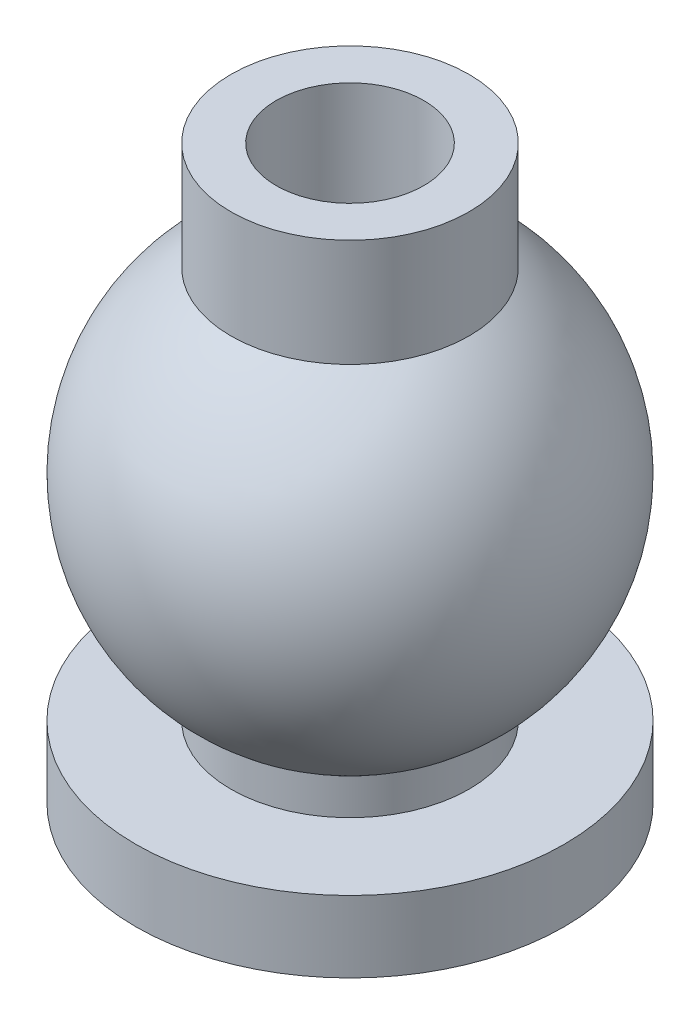
SolidWorks part; units mm, degrees
ref_plane "Front Plane" through (0, 0, 0) normal (0, 0, 1) x (1, 0, 0)
ref_plane "Top Plane" through (0, 0, 0) normal (0, 1, 0) x (1, 0, 0)
ref_plane "Right Plane" through (0, 0, 0) normal (1, 0, 0) x (0, 0, -1)
sketch "Sketch1" plane through (0, 0, 0) normal (0, 0, 1) x (1, 0, 0)
  line L0 (0, 6.8365) -> (0, -6) construction
  line L1 (1.55, -6) -> (4.5, -6)
  line L2 (4.5, -6) -> (4.5, -4.5)
  line L3 (4.5, -4.5) -> (2.5, -4.5)
  line L4 (2.5, -4.5) -> (2.5, -3.7417)
  line L5 (1.55, -6) -> (1.55, 6)
  line L6 (1.55, 6) -> (2.5, 6)
  line L7 (2.5, 6) -> (2.5, 3.7417)
  line L8 (6.0138, -6) -> (-2.0045, -6) construction
  arc A0 (2.5, -3.7417) -> (2.5, 3.7417) centre (0, 0) ccw
  dimension "D1" = 9
  dimension "D2" = 6
  dimension "D3" = 2.5
  dimension "D4" = 1.55
  dimension "D5" = 6
revolve "Revolve1" add sketch "Sketch1" angle 360 about L0
